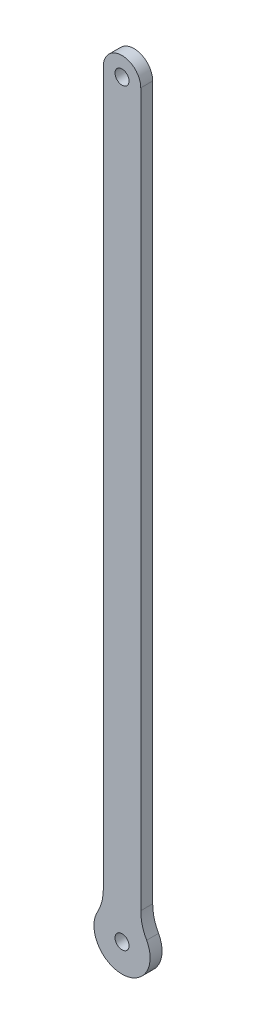
SolidWorks part; units mm, degrees
ref_plane "Front Plane" through (0, 0, 0) normal (0, 0, 1) x (1, 0, 0)
ref_plane "Top Plane" through (0, 0, 0) normal (0, 1, 0) x (1, 0, 0)
ref_plane "Right Plane" through (0, 0, 0) normal (1, 0, 0) x (0, 0, -1)
sketch "Model" plane through (0, 0, 0) normal (0, 0, 1) x (1, 0, 0)
  line L0 (-4, 8.512) -> (-4, 7.746)
  line L1 (4, 8.7857) -> (4, 7.746)
  line L11 (-4, 160) -> (-4, 8.512)
  line L12 (4, 160) -> (4, 8.7857)
  circle A0 centre (0, 0) radius 1.5
  arc A1 (-5.25, 2.9047) -> (5.25, 2.9047) centre (0, 0) ccw
  arc A2 (-4, 7.746) -> (-5.25, 2.9047) centre (-14, 7.746) cw
  arc A3 (4, 7.746) -> (5.25, 2.9047) centre (14, 7.746) ccw
  circle A6 centre (0, 160) radius 1.5
  arc A7 (4, 160) -> (-4, 160) centre (0, 160) ccw
  dimension "D1" = 3
  dimension "D2" = 12
  dimension "D15" = 3
  dimension "D5" = 10
  dimension "D3" = 4
  dimension "D4" = 4
  dimension "D16" = 160
extrude "Boss-Extrude1" add sketch "Model" along normal blind 2.55
